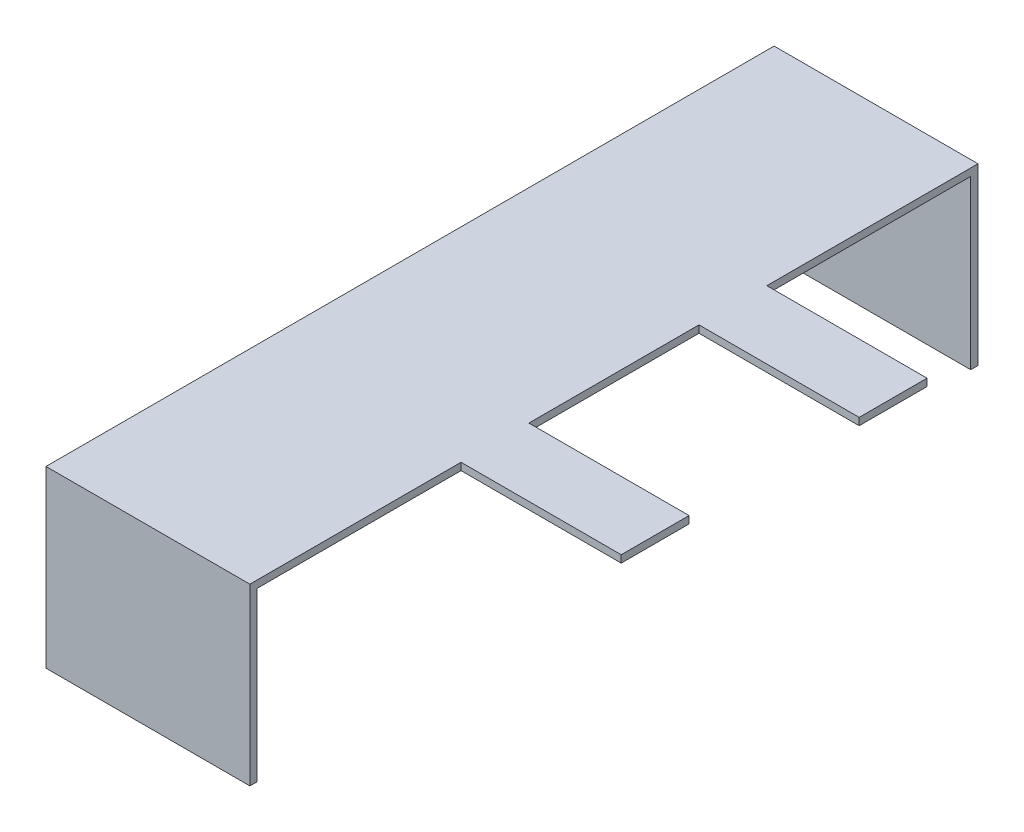
SolidWorks part; units mm, degrees
ref_plane "Front Plane" through (0, 0, 0) normal (0, 0, 1) x (1, 0, 0)
ref_plane "Top Plane" through (0, 0, 0) normal (0, 1, 0) x (1, 0, 0)
ref_plane "Right Plane" through (0, 0, 0) normal (1, 0, 0) x (0, 0, -1)
sketch "Croquis1" plane through (0, 0, 0) normal (0, 1, 0) x (1, 0, 0)
  line L1 (0, 0) -> (14, 0)
  line L2 (0, 0) -> (0, 49)
  line L3 (0, 49) -> (14, 49)
  line L5 (25, 35) -> (14, 35)
  line L7 (14, 30.34) -> (25, 30.34)
  line L9 (14, 35) -> (14, 49)
  line L10 (25, 35) -> (25, 30.34)
  line L15 (14, 14) -> (14, 0)
  line L16 (14, 14) -> (25, 14)
  line L17 (25, 14) -> (25, 18.66)
  line L18 (25, 18.66) -> (14, 18.66)
  line L19 (14, 30.34) -> (14, 18.66)
  dimension "D1" = 25
  dimension "D2" = 14
  dimension "D3" = 4.66
  dimension "D4" = 14
  dimension "D5" = 14
  dimension "D6" = 4.66
  dimension "D7" = 14
extrude "Saliente-Extruir1" add sketch "Croquis1" along normal blind 0.5
sketch "Croquis2" plane through (14, 0, 0) normal (1, 0, 0) x (0, 0, -1)
  line L0 (0, 0.5) -> (-0.5, 0.5)
  line L1 (-0.5, 0.5) -> (-0.5, -11.5)
  line L2 (-0.5, -11.5) -> (0, -11.5)
  line L3 (0, -11.5) -> (0, 0)
  line L4 (0, 0) -> (0, 0.5)
  line L5 (49.5, 0.5) -> (49.5, -11.5)
  line L6 (49.5, -11.5) -> (49, -11.5)
  line L7 (49, 0) -> (49, 0.5)
  line L11 (49, 0.5) -> (49.5, 0.5)
  line L12 (49, -11.5) -> (49, 0)
  dimension "D1" = 12
extrude "Saliente-Extruir2" add sketch "Croquis2" against normal through all
